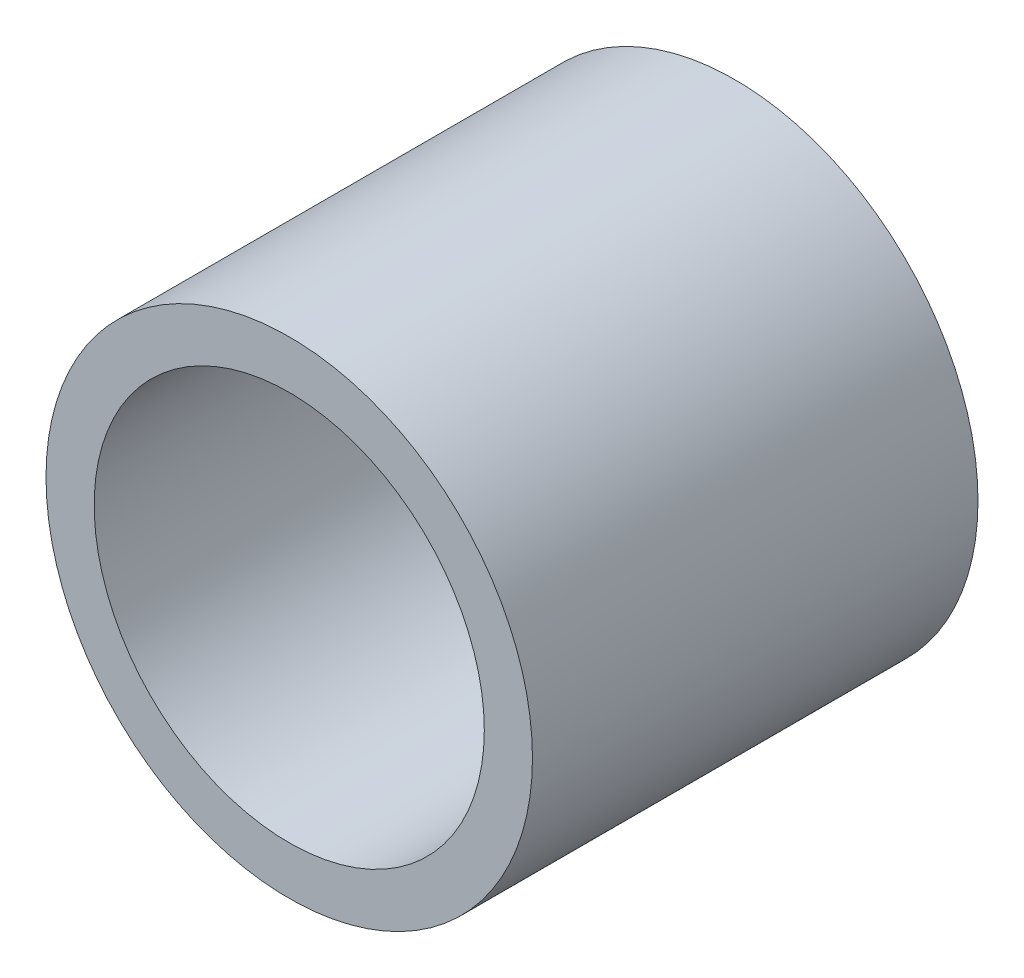
SolidWorks part; units mm, degrees
ref_plane "Front Plane" through (0, 0, 0) normal (0, 0, 1) x (1, 0, 0)
ref_plane "Top Plane" through (0, 0, 0) normal (0, 1, 0) x (1, 0, 0)
ref_plane "Right Plane" through (0, 0, 0) normal (1, 0, 0) x (0, 0, -1)
sketch "Sketch1" plane through (0, 0, 0) normal (0, 0, 1) x (1, 0, 0)
  circle A0 centre (0, 0) radius 4.05
  dimension "D1" = 8.1
extrude "Extrude-Thin1" add sketch "Sketch1" along normal blind 9.25 thin
